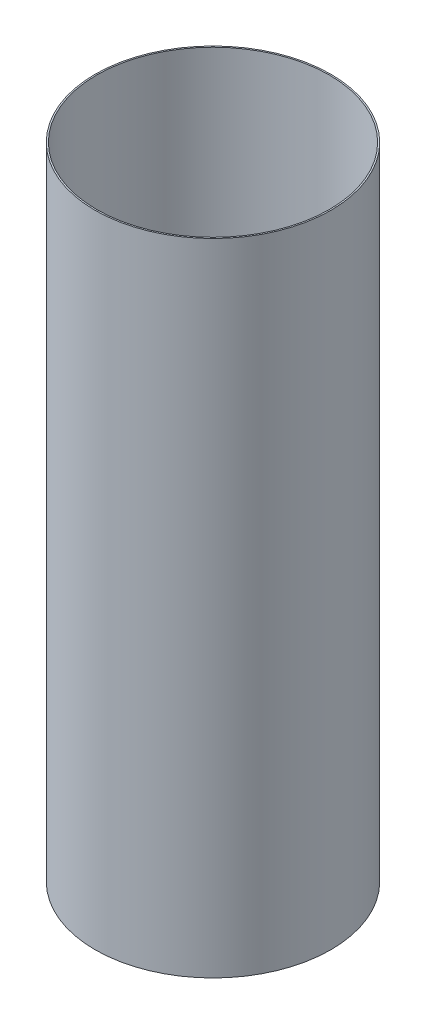
SolidWorks part; units mm, degrees
ref_plane "Front Plane" through (0, 0, 0) normal (0, 0, 1) x (1, 0, 0)
ref_plane "Top Plane" through (0, 0, 0) normal (0, 1, 0) x (1, 0, 0)
ref_plane "Right Plane" through (0, 0, 0) normal (1, 0, 0) x (0, 0, -1)
sketch "Sketch1" plane through (0, 0, 0) normal (0, 1, 0) x (1, 0, 0)
  circle A0 centre (0, 0) radius 4050
  circle A1 centre (0, 0) radius 4000
extrude "Boss-Extrude1" add sketch "Sketch1" along normal blind 22000
